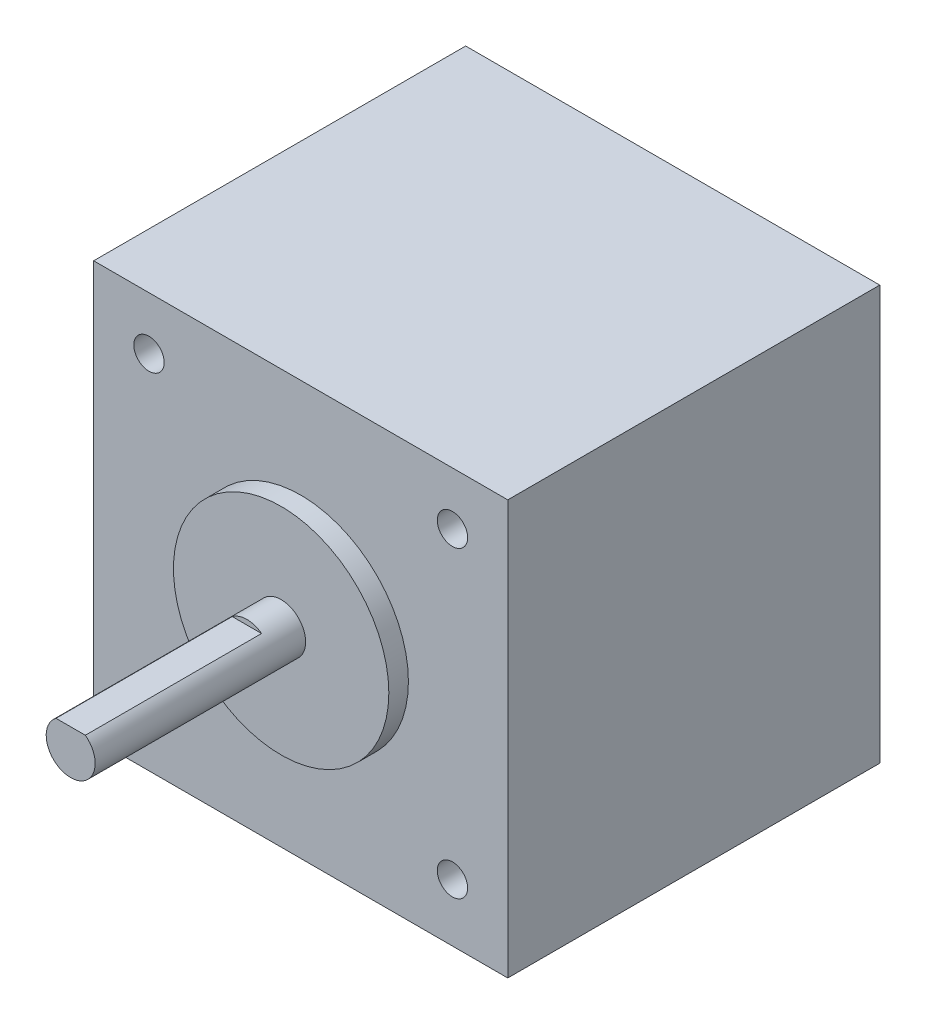
SolidWorks part; units mm, degrees
ref_plane "Front Plane" through (0, 0, 0) normal (0, 0, 1) x (1, 0, 0)
ref_plane "Top Plane" through (0, 0, 0) normal (0, 1, 0) x (1, 0, 0)
ref_plane "Right Plane" through (0, 0, 0) normal (1, 0, 0) x (0, 0, -1)
sketch "Sketch1" plane through (0, 0, 0) normal (0, 0, 1) x (1, 0, 0)
  line L1 (0, 0) -> (42.3, 0)
  line L2 (0, 0) -> (0, 42.3)
  line L3 (0, 42.3) -> (42.3, 42.3)
  line L4 (42.3, 0) -> (42.3, 42.3)
  dimension "D1" = 42.3
  dimension "D2" = 42.3
extrude "Boss-Extrude1" add sketch "Sketch1" along normal blind 38
sketch "Sketch2" plane through (0, 0, 38) normal (0, 0, 1) x (1, 0, 0)
  line L0 (0, 42.3) -> (42.3, 0) construction
  line L1 (0, 0) -> (42.3, 42.3) construction
  circle A0 centre (21.15, 21.15) radius 11
  dimension "D1" = 22
extrude "Boss-Extrude2" add sketch "Sketch2" along normal blind 2 contours A0
sketch "Sketch3" plane through (0, 0, 40) normal (0, 0, 1) x (1, 0, 0)
  line L0 (21.15, 18.9) -> (21.15, 23.4) construction
  line L1 (21.15, 32.15) -> (21.15, 10.15) construction
  circle A2 centre (21.15, 21.4) radius 2.5
  circle A3 centre (21.15, 21.15) radius 11 construction
  circle A4 centre (21.15, 21.15) radius 11 construction
  dimension "D1" = 5
  dimension "D2" = 4.5
extrude "Boss-Extrude4" add sketch "Sketch3" along normal blind 21.5
sketch "Sketch4" plane through (0, 0, 61.5) normal (0, 0, 1) x (1, 0, 0)
  line L0 (21.15, 18.9) -> (21.15, 23.4) construction
  line L1 (21.15, 23.4) -> (22.65, 23.4)
  line L2 (21.15, 23.4) -> (19.65, 23.4)
  circle A0 centre (21.15, 21.4) radius 2.5 construction
  circle A1 centre (21.15, 21.4) radius 2.5 construction
  arc A2 (22.65, 23.4) -> (19.65, 23.4) centre (21.15, 21.4) ccw
  dimension "D1" = 4.5
extrude "Cut-Extrude1" cut sketch "Sketch4" against normal blind 18
sketch "Sketch5" plane through (0, 0, 38) normal (0, 0, 1) x (1, 0, 0)
  line L1 (5.65, 5.9) -> (36.65, 5.9) construction
  line L2 (5.65, 5.9) -> (5.65, 36.9) construction
  line L3 (5.65, 36.9) -> (36.65, 36.9) construction
  line L4 (36.65, 5.9) -> (36.65, 36.9) construction
  line L5 (5.65, 5.9) -> (36.65, 36.9) construction
  line L6 (5.65, 36.9) -> (36.65, 5.9) construction
  circle A0 centre (5.65, 36.9) radius 1.55
  circle A1 centre (36.65, 36.9) radius 1.55
  circle A2 centre (36.65, 5.9) radius 1.55
  circle A3 centre (5.65, 5.9) radius 1.55
  point P0 (21.15, 21.4)
  dimension "D3" = 3.1
  dimension "D1" = 31
  dimension "D2" = 31
extrude "Cut-Extrude2" cut sketch "Sketch5" against normal blind 4.5
sketch "Sketch6" plane through (0, 0, 0) normal (0, 0, -1) x (-1, 0, 0)
  line L4 (0, 0) -> (0, 42.3)
  line L5 (0, 42.3) -> (-42.3, 42.3)
  line L6 (-42.3, 42.3) -> (-42.3, 0)
  line L7 (-42.3, 0) -> (0, 0)
  line L8 (0, 0) -> (0, 42.3)
  line L9 (0, 42.3) -> (-42.3, 42.3)
  line L10 (-42.3, 42.3) -> (-42.3, 0)
  line L11 (-42.3, 0) -> (0, 0)
  circle A0 centre (-5.65, 36.9) radius 1.55 construction
  circle A1 centre (-36.65, 36.9) radius 1.55 construction
  circle A2 centre (-36.65, 5.9) radius 1.55 construction
  circle A3 centre (-5.65, 5.9) radius 1.55 construction
  circle A4 centre (-5.65, 36.9) radius 1.55
  circle A5 centre (-36.65, 36.9) radius 1.55
  circle A6 centre (-36.65, 5.9) radius 1.55
  circle A7 centre (-5.65, 5.9) radius 1.55
  dimension "D1" = 0
extrude "Cut-Extrude3" cut sketch "Sketch6" against normal blind 4.5 flip side to cut
